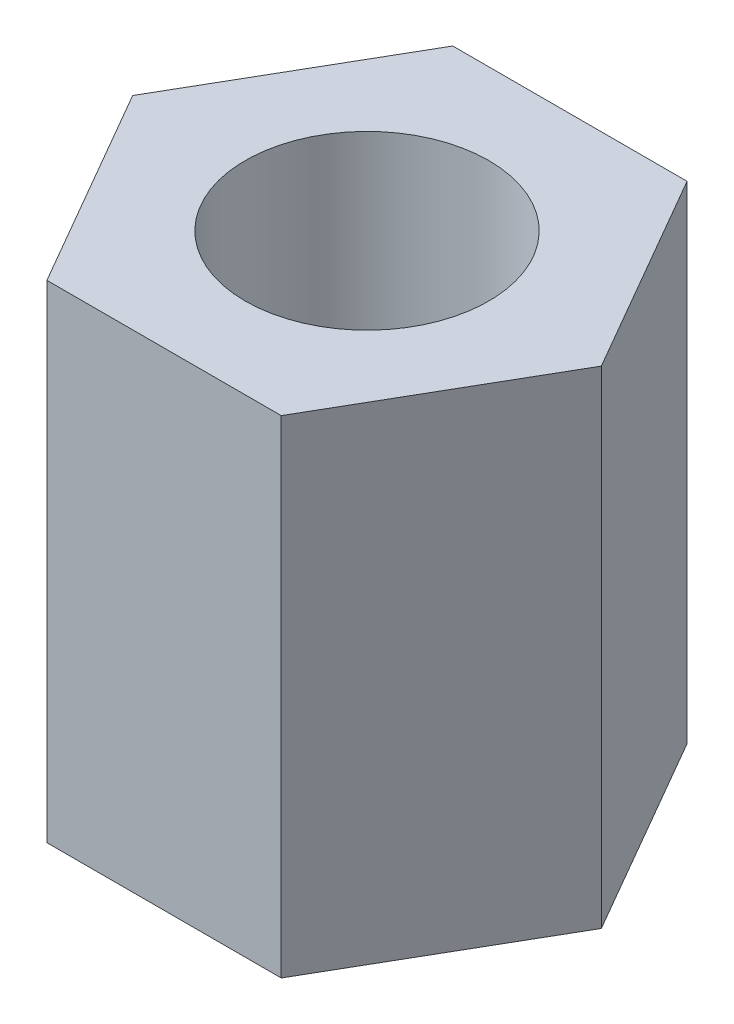
SolidWorks part; units mm, degrees
material "ABS"
ref_plane "Alzado" through (0, 0, 0) normal (0, 0, 1) x (1, 0, 0)
ref_plane "Planta" through (0, 0, 0) normal (0, 1, 0) x (1, 0, 0)
ref_plane "Vista lateral" through (0, 0, 0) normal (1, 0, 0) x (0, 0, -1)
sketch "Croquis1" plane through (0, 0, 0) normal (0, 1, 0) x (1, 0, 0)
  line L1 (1.4434, -2.5) -> (2.8868, 0)
  line L2 (2.8868, 0) -> (1.4434, 2.5)
  line L3 (1.4434, 2.5) -> (-1.4434, 2.5)
  line L4 (-1.4434, 2.5) -> (-2.8868, 0)
  line L5 (-2.8868, 0) -> (-1.4434, -2.5)
  line L6 (-1.4434, -2.5) -> (1.4434, -2.5)
  circle A0 centre (0, 0) radius 2.5 construction
  circle A1 centre (0, 0) radius 1.5
  dimension "D2" = 3
  dimension "D1" = 5
extrude "Saliente-Extruir1" add sketch "Croquis1" along normal mid plane 12
sketch "草图1" plane through (0, 6, 0) normal (0, 1, 0) x (1, 0, 0)
  line L6 (-1.4434, -2.5) -> (1.4434, -2.5)
  line L7 (1.4434, -2.5) -> (2.8868, 0)
  line L8 (2.8868, 0) -> (1.4434, 2.5)
  line L9 (1.4434, 2.5) -> (-1.4434, 2.5)
  line L10 (-1.4434, 2.5) -> (-2.8868, 0)
  line L11 (-2.8868, 0) -> (-1.4434, -2.5)
  line L12 (-1.4434, -2.5) -> (1.4434, -2.5)
  line L13 (1.4434, -2.5) -> (2.8868, 0)
  line L14 (2.8868, 0) -> (1.4434, 2.5)
  line L15 (1.4434, 2.5) -> (-1.4434, 2.5)
  line L16 (-1.4434, 2.5) -> (-2.8868, 0)
  line L17 (-2.8868, 0) -> (-1.4434, -2.5)
  circle A0 centre (0, 0) radius 1.5 construction
  circle A1 centre (0, 0) radius 1.5
  dimension "D1" = 0
extrude "切除-拉伸1" cut sketch "草图1" against normal blind 6
